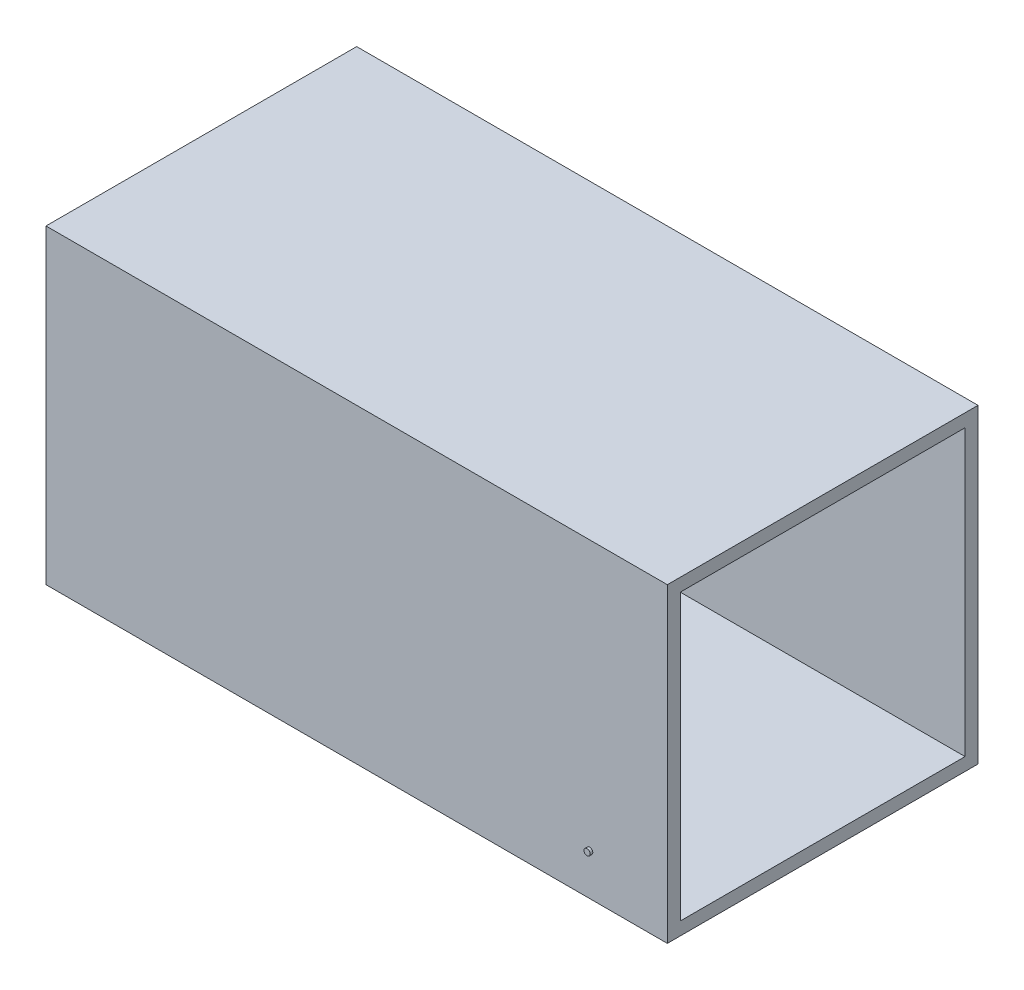
SolidWorks part; units mm, degrees
ref_plane "Front Plane" through (0, 0, 0) normal (0, 0, 1) x (1, 0, 0)
ref_plane "Top Plane" through (0, 0, 0) normal (0, 1, 0) x (1, 0, 0)
ref_plane "Right Plane" through (0, 0, 0) normal (1, 0, 0) x (0, 0, -1)
sketch "Sketch1" plane through (0, 0, 0) normal (1, 0, 0) x (0, 0, -1)
  line L1 (0, 0) -> (600, 0)
  line L2 (0, 0) -> (0, 600)
  line L3 (0, 600) -> (600, 600)
  line L4 (600, 0) -> (600, 600)
  dimension "D1" = 600
  dimension "D2" = 600
extrude "Boss-Extrude1" add sketch "Sketch1" along normal blind 1200
shell "Shell1" thickness 25
sketch "Sketch2" plane through (0, 0, 0) normal (0, 0, 1) x (1, 0, 0)
  line L0 (1200, 0) -> (0, 0) construction
  line L1 (1200, 600) -> (1200, 0) construction
  circle A0 centre (1050, 80) radius 6
  circle A1 centre (1000, 642) radius 6 construction
  dimension "D1" = 80
  dimension "D2" = 150
extrude "Boss-Extrude2" add sketch "Sketch2" along normal up to vertex (5 mm away)
ref_plane "Plane1" through (0, 0, -300) normal (0, 0, 1) x (1, 0, 0)
mirror "Mirror1" about plane through (0, 0, -300) normal (0, 0, 1) of "Boss-Extrude2"
